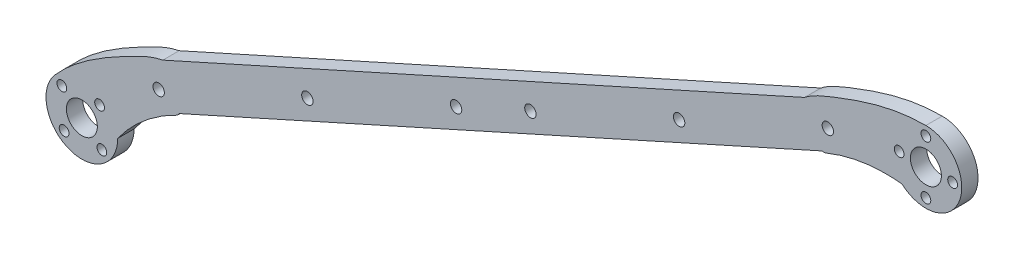
SolidWorks part; units mm, degrees
ref_plane "Front Plane" through (0, 0, 0) normal (0, 0, 1) x (1, 0, 0)
ref_plane "Top Plane" through (0, 0, 0) normal (0, 1, 0) x (1, 0, 0)
ref_plane "Right Plane" through (0, 0, 0) normal (1, 0, 0) x (0, 0, -1)
sketch "Sketch1" plane through (0, 0, 0) normal (0, 0, 1) x (1, 0, 0)
  line L1 (-134.9965, -45.7877) -> (-137.0059, -41.3187) construction
  line L12 (-228.9833, -100.3277) -> (-31.8237, -11.6776)
  line L14 (-37.2233, -0.1609) -> (-234.0148, -88.6454)
  arc A1 (-30.5499, -11.5956) -> (-31.8237, -11.6776) centre (-31.3087, -9.7451) cw
  circle A5 centre (-8.2, 0) radius 1.5
  circle A6 centre (0, 8.2) radius 1.5
  circle A7 centre (0, -8.2) radius 1.5
  circle A8 centre (8.2, 0) radius 1.5
  arc A9 (-7.3321, -8.2) -> (0, 11) centre (0, 0) ccw
  circle A10 centre (0, 0) radius 4.75
  circle A24 centre (-258.8386, -116.3831) radius 4.75
  arc A25 (-247.8387, -116.3404) -> (-267.067, -109.0829) centre (-258.8386, -116.3831) cw
  circle A26 centre (-264.2805, -122.517) radius 1.5
  circle A27 centre (-252.7047, -121.8251) radius 1.5
  circle A28 centre (-264.9725, -110.9412) radius 1.5
  circle A29 centre (-253.3966, -110.2492) radius 1.5
  arc A30 (-229.89, -101.226) -> (-228.9833, -100.3277) centre (-230.7707, -99.4304) ccw
  circle A33 centre (-75.6741, -25.316) radius 1.75
  circle A38 centre (-30.0718, -4.8116) radius 1.75
  circle A39 centre (-121.2763, -45.8204) radius 1.75
  circle A40 centre (-235.2821, -97.0815) radius 1.75
  circle A41 centre (-189.6798, -76.5771) radius 1.75
  circle A42 centre (-144.0775, -56.0726) radius 1.75
  spline S0 degree 3 poles (-7.3321, -8.2) (-15.2617, -7.3782) (-23.0287, -8.5117) (-30.5499, -11.5956) knots 0 0 0 0 0.928486 0.928486 0.928486 0.928486
  spline S1 degree 3 poles (-37.2233, -0.1609) (-34.7332, 1.803) (-22.3319, 6.9275) (-10.1101, 10.9882) (0, 11) knots 0.039876 0.039876 0.039876 0.039876 0.276467 1 1 1 1
  spline S2 degree 3 poles (-234.0148, -88.6454) (-237.1364, -89.2047) (-249.2, -95.0805) (-260.3486, -101.5279) (-267.067, -109.0829) knots 0.039876 0.039876 0.039876 0.039876 0.276467 1 1 1 1
  spline S3 degree 3 poles (-247.8387, -116.3404) (-243.1909, -109.8634) (-237.1883, -104.8056) (-229.89, -101.226) knots 0 0 0 0 0.928486 0.928486 0.928486 0.928486
  point P9 (-130.4035, -56.0027)
  point P39 (-235.2821, -97.0815)
  point P59 (-135.619, -44.4032)
  dimension "D1" = 2
extrude "Boss-Extrude1" add sketch "Sketch1" along normal blind 5
